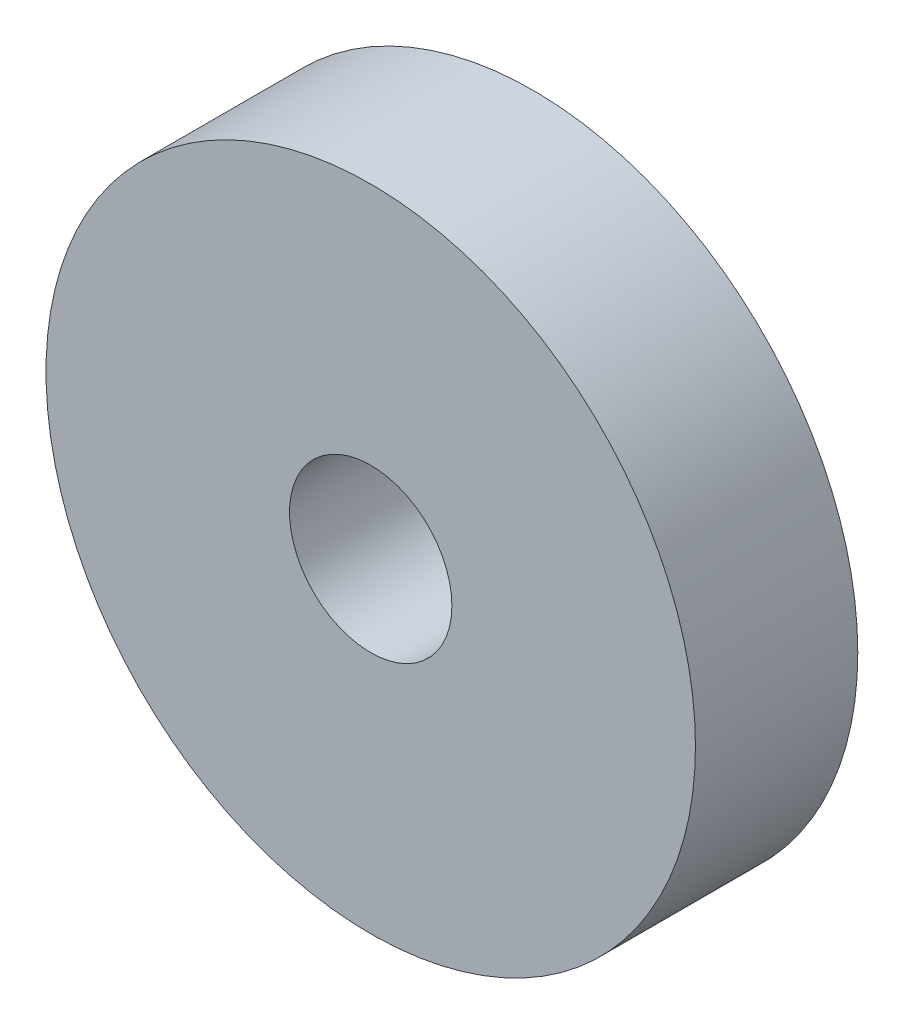
SolidWorks part; units mm, degrees
ref_plane "Front Plane" through (0, 0, 0) normal (0, 0, 1) x (1, 0, 0)
ref_plane "Top Plane" through (0, 0, 0) normal (0, 1, 0) x (1, 0, 0)
ref_plane "Right Plane" through (0, 0, 0) normal (1, 0, 0) x (0, 0, -1)
sketch "Sketch1" plane through (0, 0, 0) normal (0, 0, 1) x (1, 0, 0)
  circle A0 centre (0, 0) radius 12.7
  circle A1 centre (0, 0) radius 3.175
  dimension "D1" = 6.35
  dimension "D2" = 25.4
extrude "Boss-Extrude1" add sketch "Sketch1" along normal blind 6.35
